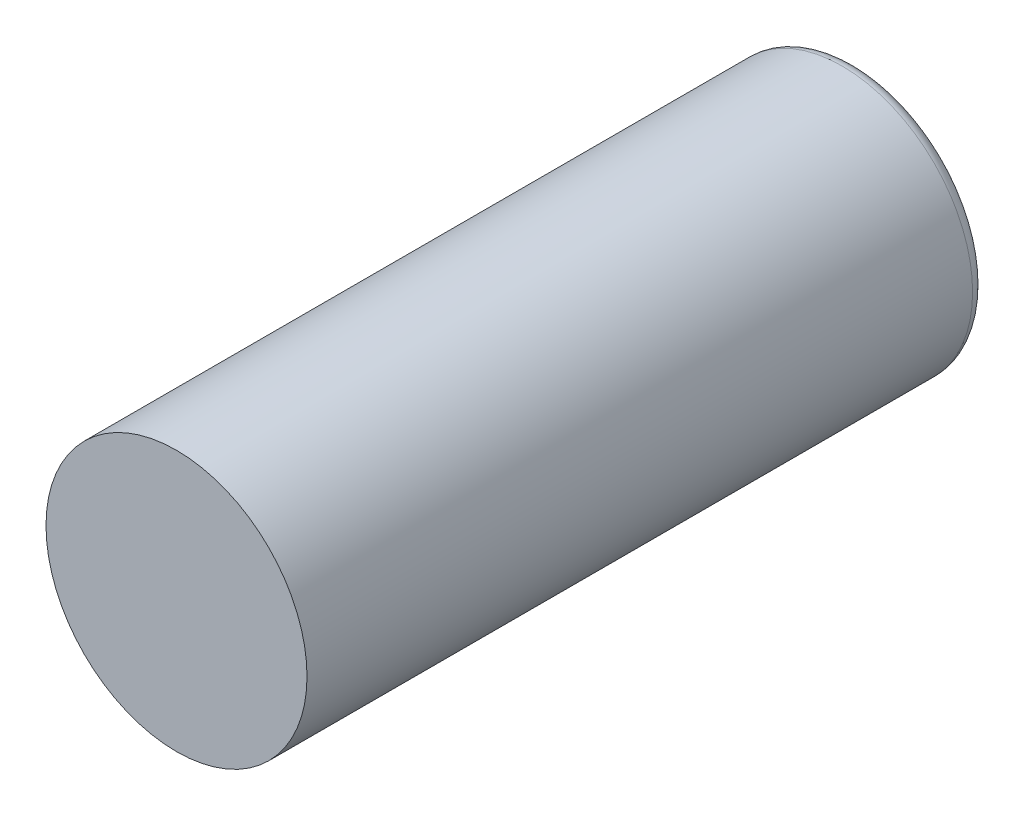
SolidWorks part; units mm, degrees
material "Gray Cast Iron"
ref_plane "Front Plane" through (0, 0, 0) normal (0, 0, 1) x (1, 0, 0)
ref_plane "Top Plane" through (0, 0, 0) normal (0, 1, 0) x (1, 0, 0)
ref_plane "Right Plane" through (0, 0, 0) normal (1, 0, 0) x (0, 0, -1)
sketch "Sketch2" plane through (0, 0, 0) normal (0, 0, 1) x (1, 0, 0)
  circle A0 centre (0, 0) radius 2.5
  dimension "D1" = 5
extrude "Boss-Extrude1" add sketch "Sketch2" along normal blind 13
cosmetic thread "Cosmetic Thread1" parameters "D1"=4, "D2"=4.11
fillet "Fillet1" radius 0.25 1 edges at (2.5, 0, 0)
